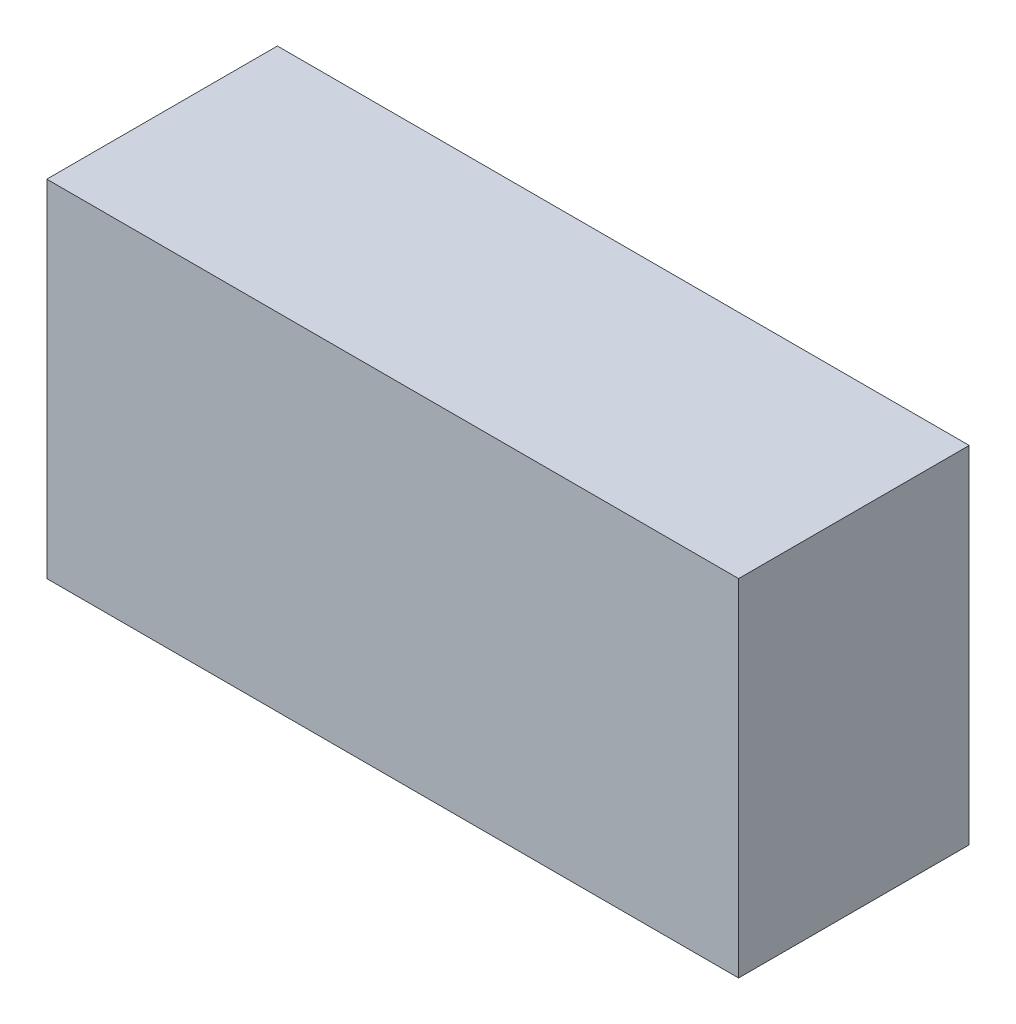
SolidWorks part; units mm, degrees
ref_plane "Front Plane" through (0, 0, 0) normal (0, 0, 1) x (1, 0, 0)
ref_plane "Top Plane" through (0, 0, 0) normal (0, 1, 0) x (1, 0, 0)
ref_plane "Right Plane" through (0, 0, 0) normal (1, 0, 0) x (0, 0, -1)
sketch "Sketch1" plane through (0, 0, 0) normal (0, 0, 1) x (1, 0, 0)
  line L1 (0, 0) -> (60, 0)
  line L2 (0, 0) -> (0, -30)
  line L3 (0, -30) -> (60, -30)
  line L4 (60, 0) -> (60, -30)
  dimension "D1" = 60
  dimension "D2" = 30
extrude "Boss-Extrude1" add sketch "Sketch1" along normal blind 20 contours L1 L4 L3 L2
